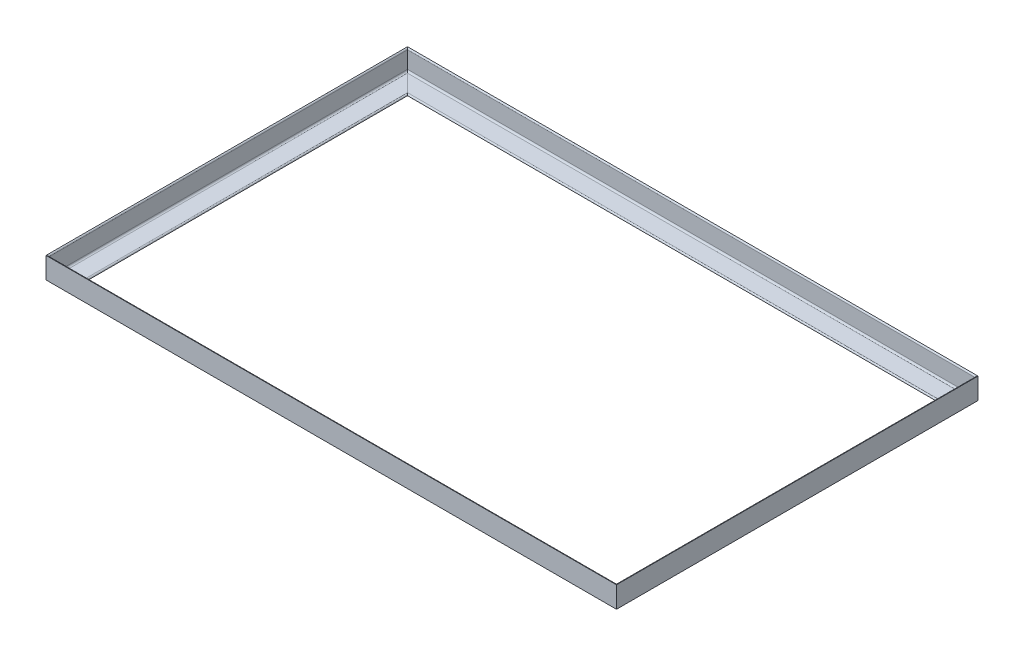
SolidWorks part; units mm, degrees
ref_plane "Alzado" through (0, 0, 0) normal (0, 0, 1) x (1, 0, 0)
ref_plane "Planta" through (0, 0, 0) normal (0, 1, 0) x (1, 0, 0)
ref_plane "Vista lateral" through (0, 0, 0) normal (1, 0, 0) x (0, 0, -1)
sketch "Croquis1" plane through (0, 0, 0) normal (0, 1, 0) x (1, 0, 0)
  line L1 (-1365, 865) -> (1365, 865)
  line L2 (-1365, 865) -> (-1365, -865)
  line L3 (-1365, -865) -> (1365, -865)
  line L4 (1365, 865) -> (1365, -865)
  line L5 (-1365, 865) -> (1365, -865) construction
  line L6 (-1365, -865) -> (1365, 865) construction
  point P0 (0, 0)
  dimension "D1" = 2730
  dimension "D2" = 1730
other "Hierro angular 3 X 2 X 0.25(1)"
ref_plane "Plano1" through (-1365, 0, -865) normal (0, 0, 1) x (1, 0, 0)
sketch "Sketch1" plane through (-1365, 0, -865) normal (0, 0, 1) x (1, 0, 0)
  line L0 (0, 0) -> (0, 101.6)
  line L1 (0, 101.6) -> (0.0051, 101.6)
  line L2 (6.35, 95.2551) -> (6.35, 14.2875)
  line L3 (14.2875, 6.35) -> (95.2551, 6.35)
  line L4 (101.6, 0.0051) -> (101.6, 0)
  line L5 (101.6, 0) -> (0, 0)
  arc A0 (101.6, 0.0051) -> (95.2551, 6.35) centre (95.2551, 0.0051) ccw
  arc A1 (0.0051, 101.6) -> (6.35, 95.2551) centre (0.0051, 95.2551) cw
  arc A2 (14.2875, 6.35) -> (6.35, 14.2875) centre (14.2875, 14.2875) cw
  point P10 (50.8, 0)
  point P14 (0, 50.8)
  point P15 (6.35, 50.8)
  point P16 (50.8, 6.35)
  point P17 (6.35, 101.6)
  point P18 (101.6, 6.35)
  point P19 (0, 0)
  dimension "D2" = 0.0051
  dimension "D3" = 101.6
  dimension "Radius_1" = 7.9375
  dimension "D1" = 6.35
  dimension "H_leg" = 101.6
